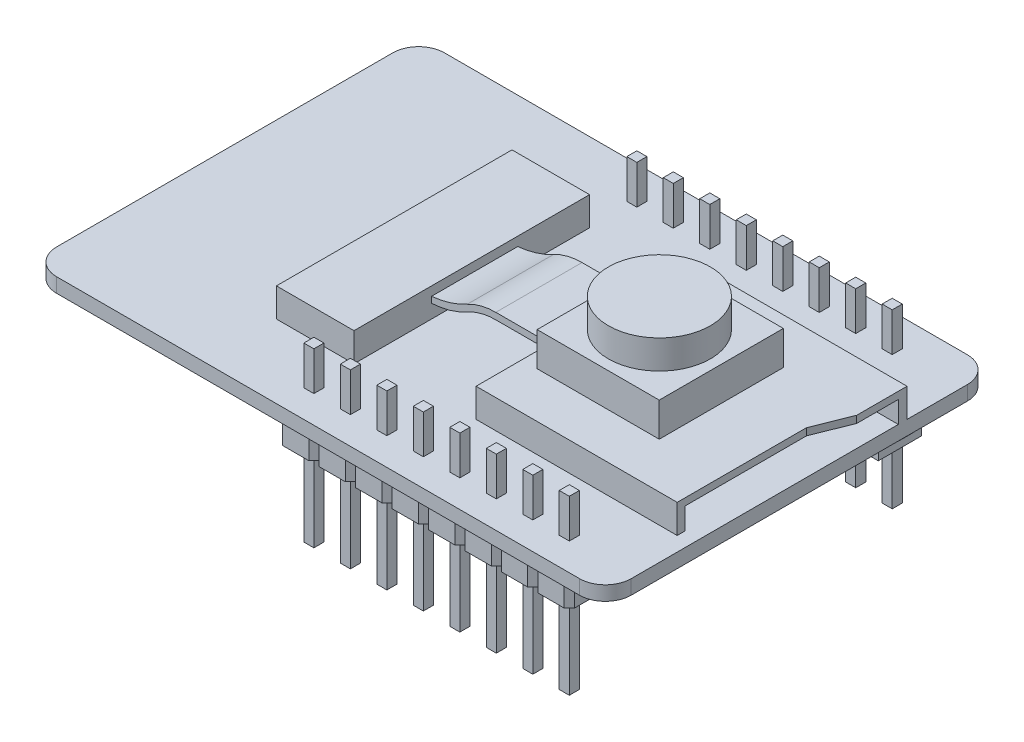
SolidWorks part; units mm, degrees
ref_plane "前视基准面" through (0, 0, 0) normal (0, 0, 1) x (1, 0, 0)
ref_plane "上视基准面" through (0, 0, 0) normal (0, 1, 0) x (1, 0, 0)
ref_plane "右视基准面" through (0, 0, 0) normal (1, 0, 0) x (0, 0, -1)
sketch "草图1" plane through (0, 0, 0) normal (0, 1, 0) x (1, 0, 0)
  line L0 (-20, 13.5) -> (20, 13.5)
  line L1 (-20, 13.5) -> (-20, -13.5)
  line L2 (20, 13.5) -> (20, -13.5)
  line L3 (-20, -13.5) -> (20, -13.5)
  line L4 (-20, 13.5) -> (20, -13.5) construction
  line L5 (20, 13.5) -> (-20, -13.5) construction
  point P1 (0, 0)
extrude "凸台-拉伸1" add sketch "草图1" along normal blind 1
fillet "圆角1" radius 1.8 4 edges at (-20, 0.5, 13.5) (-20, 0.5, -13.5) (20, 0.5, -13.5) (20, 0.5, 13.5)
sketch "草图4" plane through (0, 0, 0) normal (0, -1, 0) x (1, 0, 0)
  line L0 (-20, -11.7) -> (-20, 11.7) construction
  line L1 (-20, 9) -> (5.5, 9)
  line L2 (-20, 9) -> (-20, -9)
  line L3 (-20, -9) -> (5.5, -9)
  line L4 (5.5, 9) -> (5.5, -9)
  line L5 (-24.7231, 0) -> (25.6877, 0) construction
  dimension "D1" = 18
  dimension "D2" = 25.5
extrude "esp32底板" add sketch "草图4" along normal blind 1
sketch "草图5" plane through (0, -1, 0) normal (0, -1, 0) x (1, 0, 0)
  line L0 (-27.2904, 0) -> (11.6436, 0) construction
  line L1 (-12.65, 2.15) -> (-9.41, 2.15)
  line L2 (-12.65, 2.15) -> (-12.65, -7.85)
  line L3 (-12.65, -7.85) -> (-9.0798, -7.85)
  line L5 (-9.41, 7.85) -> (4.35, 7.85)
  line L6 (-9.41, 7.85) -> (-9.41, 2.15)
  line L7 (-9.0798, -7.85) -> (4.35, -7.85)
  line L8 (4.35, 7.85) -> (4.35, -7.85)
  line L9 (5.5, -9) -> (5.5, 9) construction
  dimension "D1" = 10
  dimension "D2" = 15.7
  dimension "D3" = 3.24
  dimension "D4" = 5.7
  dimension "D5" = 17
  dimension "D6" = 1.15
extrude "esp32外壳" add sketch "草图5" along normal blind 2.4
sketch "草图6" plane through (0, -1, 0) normal (0, -1, 0) x (1, 0, 0)
  line L0 (-20, 9) -> (-20, -9) construction
  line L1 (-14, 8) -> (-11.2, 8)
  line L2 (-14, 8) -> (-14, 5.6)
  line L3 (-14, 5.6) -> (-11.2, 5.6)
  line L4 (-11.2, 8) -> (-11.2, 5.6)
  line L5 (5.5, 9) -> (-20, 9) construction
  dimension "D1" = 6
  dimension "D2" = 1
  dimension "D3" = 2.4
  dimension "D4" = 2.8
extrude "天线座子地" add sketch "草图6" along normal blind 0.5
sketch "草图7" plane through (0, -1.5, 0) normal (0, -1, 0) x (1, 0, 0)
  circle A0 centre (-12.6345, 6.845) radius 0.101
extrude "天线座子针" add sketch "草图7" along normal blind 0.5
sketch "草图8" plane through (0, -1.5, 0) normal (0, -1, 0) x (1, 0, 0)
  circle A0 centre (-12.6345, 6.845) radius 1
  circle A1 centre (-12.6345, 6.845) radius 0.7746
  dimension "D1" = 2
extrude "天线座子" add sketch "草图8" along normal blind 0.5
sketch "草图9" plane through (0, -1, 0) normal (0, -1, 0) x (1, 0, 0)
  line L0 (-15.5448, -7.9938) -> (-18.5448, -7.9938)
  line L1 (-18.5448, -7.9938) -> (-18.5448, -4.9938)
  line L2 (-18.5448, -4.9938) -> (-15.5448, -4.9938)
  line L3 (-15.5448, -4.9938) -> (-15.5448, -1.9938)
  line L4 (-15.5448, -1.9938) -> (-18.5448, -1.9938)
  line L5 (-18.5448, -1.9938) -> (-18.5448, 1.0062)
  line L6 (-18.5448, 1.0062) -> (-15.5448, 1.0062)
  line L7 (-15.5448, 1.0062) -> (-15.5448, 4.0062)
  line L8 (-15.5448, 4.0062) -> (-18.5448, 4.0062)
  line L9 (-18.5448, 4.0062) -> (-18.5448, 7.0062)
  line L10 (-18.5448, 7.0062) -> (-15.5448, 7.0062)
  line L11 (-15.5448, 7.0062) -> (-15.5448, 8.3405)
  line L12 (-15.5448, 8.3405) -> (-19.2709, 8.3405)
  line L13 (-19.2709, 8.3405) -> (-19.2709, 3.4012)
  line L14 (-19.2709, 3.4012) -> (-16.0214, 3.4012)
  line L15 (-16.0214, 3.4012) -> (-16.0214, 1.5814)
  line L16 (-16.0214, 1.5814) -> (-19.2709, 1.5814)
  line L17 (-19.2709, 1.5814) -> (-19.2709, -2.7513)
  line L18 (-19.2709, -2.7513) -> (-16.0214, -2.7513)
  line L19 (-16.0214, -2.7513) -> (-16.0214, -4.3977)
  line L20 (-16.0214, -4.3977) -> (-19.2709, -4.3977)
  line L21 (-19.2709, -4.3977) -> (-19.2709, -8.6004)
  line L22 (-19.2709, -8.6004) -> (-13.8983, -8.6004)
  line L23 (-13.8983, -8.6004) -> (-13.8983, -7.9938)
  line L24 (-13.8983, -7.9938) -> (-15.5448, -7.9938)
extrude "天线" add sketch "草图9" along normal blind 0.1
sketch "草图10" plane through (0, 0, 0) normal (0, -1, 0) x (1, 0, 0)
  line L0 (20, 11.7) -> (20, -11.7) construction
  line L1 (12.5, 9.4) -> (16.5, 9.4)
  line L2 (12.5, 9.4) -> (12.5, 4.4)
  line L3 (12.5, 4.4) -> (16.5, 4.4)
  line L4 (16.5, 9.4) -> (16.5, 4.4)
  line L5 (-18.2, 13.5) -> (18.2, 13.5) construction
  dimension "D1" = 4
  dimension "D2" = 5
  dimension "D3" = 3.5
  dimension "D4" = 4.1
extrude "FLASH" add sketch "草图10" along normal blind 1.5
sketch "草图2" plane through (0, 0, 0) normal (0, -1, 0) x (1, 0, 0)
  line L0 (16.5, 19.3459) -> (16.5, -19.7584) construction
  line L5 (20, 11.7) -> (20, -11.7) construction
  line L6 (-3.8208, 12.1566) -> (-3.8208, 10.3237)
  line L7 (-3.8208, 10.3237) -> (-3.4672, 9.9701)
  line L8 (-3.4672, 9.9701) -> (-1.6343, 9.9701)
  line L9 (-1.6343, 9.9701) -> (-1.2808, 10.3237)
  line L11 (-1.2808, 12.1566) -> (-1.6343, 12.5101)
  line L20 (-1.6343, 12.5101) -> (-3.4672, 12.5101)
  line L21 (-3.4672, 12.5101) -> (-3.8208, 12.1566)
  line L24 (0.9057, 12.5101) -> (-0.9272, 12.5101)
  line L25 (1.2592, 12.1566) -> (0.9057, 12.5101)
  line L27 (0.9057, 9.9701) -> (1.2592, 10.3237)
  line L28 (-0.9272, 9.9701) -> (0.9057, 9.9701)
  line L29 (-1.2808, 10.3237) -> (-0.9272, 9.9701)
  line L31 (-0.9272, 12.5101) -> (-1.2808, 12.1566)
  line L32 (3.4457, 12.5101) -> (1.6128, 12.5101)
  line L33 (3.7992, 12.1566) -> (3.4457, 12.5101)
  line L35 (3.4457, 9.9701) -> (3.7992, 10.3237)
  line L36 (1.6128, 9.9701) -> (3.4457, 9.9701)
  line L37 (1.2592, 10.3237) -> (1.6128, 9.9701)
  line L39 (1.6128, 12.5101) -> (1.2592, 12.1566)
  line L40 (5.9857, 12.5101) -> (4.1528, 12.5101)
  line L41 (6.3392, 12.1566) -> (5.9857, 12.5101)
  line L43 (5.9857, 9.9701) -> (6.3392, 10.3237)
  line L44 (4.1528, 9.9701) -> (5.9857, 9.9701)
  line L45 (3.7992, 10.3237) -> (4.1528, 9.9701)
  line L47 (4.1528, 12.5101) -> (3.7992, 12.1566)
  line L48 (8.5257, 12.5101) -> (6.6928, 12.5101)
  line L49 (8.8792, 12.1566) -> (8.5257, 12.5101)
  line L51 (8.5257, 9.9701) -> (8.8792, 10.3237)
  line L52 (6.6928, 9.9701) -> (8.5257, 9.9701)
  line L53 (6.3392, 10.3237) -> (6.6928, 9.9701)
  line L55 (6.6928, 12.5101) -> (6.3392, 12.1566)
  line L56 (11.0657, 12.5101) -> (9.2328, 12.5101)
  line L57 (11.4192, 12.1566) -> (11.0657, 12.5101)
  line L59 (11.0657, 9.9701) -> (11.4192, 10.3237)
  line L60 (9.2328, 9.9701) -> (11.0657, 9.9701)
  line L61 (8.8792, 10.3237) -> (9.2328, 9.9701)
  line L63 (9.2328, 12.5101) -> (8.8792, 12.1566)
  line L64 (13.6057, 12.5101) -> (11.7728, 12.5101)
  line L65 (13.9592, 12.1566) -> (13.6057, 12.5101)
  line L67 (13.6057, 9.9701) -> (13.9592, 10.3237)
  line L68 (11.7728, 9.9701) -> (13.6057, 9.9701)
  line L69 (11.4192, 10.3237) -> (11.7728, 9.9701)
  line L71 (11.7728, 12.5101) -> (11.4192, 12.1566)
  line L72 (16.1457, 12.5101) -> (14.3128, 12.5101)
  line L73 (16.4992, 12.1566) -> (16.1457, 12.5101)
  line L74 (16.4992, 10.3237) -> (16.4992, 12.1566)
  line L75 (16.1457, 9.9701) -> (16.4992, 10.3237)
  line L76 (14.3128, 9.9701) -> (16.1457, 9.9701)
  line L77 (13.9592, 10.3237) -> (14.3128, 9.9701)
  line L79 (14.3128, 12.5101) -> (13.9592, 12.1566)
  line L80 (-30.9826, 0) -> (35.1621, 0) construction
  line L81 (14.3128, -12.5101) -> (13.9592, -12.1566)
  line L83 (13.9592, -10.3237) -> (14.3128, -9.9701)
  line L84 (14.3128, -9.9701) -> (16.1457, -9.9701)
  line L85 (16.1457, -9.9701) -> (16.4992, -10.3237)
  line L86 (16.4992, -10.3237) -> (16.4992, -12.1566)
  line L87 (16.4992, -12.1566) -> (16.1457, -12.5101)
  line L88 (16.1457, -12.5101) -> (14.3128, -12.5101)
  line L89 (11.7728, -12.5101) -> (11.4192, -12.1566)
  line L91 (11.4192, -10.3237) -> (11.7728, -9.9701)
  line L92 (11.7728, -9.9701) -> (13.6057, -9.9701)
  line L93 (13.6057, -9.9701) -> (13.9592, -10.3237)
  line L95 (13.9592, -12.1566) -> (13.6057, -12.5101)
  line L96 (13.6057, -12.5101) -> (11.7728, -12.5101)
  line L97 (9.2328, -12.5101) -> (8.8792, -12.1566)
  line L99 (8.8792, -10.3237) -> (9.2328, -9.9701)
  line L100 (9.2328, -9.9701) -> (11.0657, -9.9701)
  line L101 (11.0657, -9.9701) -> (11.4192, -10.3237)
  line L103 (11.4192, -12.1566) -> (11.0657, -12.5101)
  line L104 (11.0657, -12.5101) -> (9.2328, -12.5101)
  line L105 (6.6928, -12.5101) -> (6.3392, -12.1566)
  line L107 (6.3392, -10.3237) -> (6.6928, -9.9701)
  line L108 (6.6928, -9.9701) -> (8.5257, -9.9701)
  line L109 (8.5257, -9.9701) -> (8.8792, -10.3237)
  line L111 (8.8792, -12.1566) -> (8.5257, -12.5101)
  line L112 (8.5257, -12.5101) -> (6.6928, -12.5101)
  line L113 (4.1528, -12.5101) -> (3.7992, -12.1566)
  line L115 (3.7992, -10.3237) -> (4.1528, -9.9701)
  line L116 (4.1528, -9.9701) -> (5.9857, -9.9701)
  line L117 (5.9857, -9.9701) -> (6.3392, -10.3237)
  line L119 (6.3392, -12.1566) -> (5.9857, -12.5101)
  line L120 (5.9857, -12.5101) -> (4.1528, -12.5101)
  line L121 (1.6128, -12.5101) -> (1.2592, -12.1566)
  line L123 (1.2592, -10.3237) -> (1.6128, -9.9701)
  line L124 (1.6128, -9.9701) -> (3.4457, -9.9701)
  line L125 (3.4457, -9.9701) -> (3.7992, -10.3237)
  line L127 (3.7992, -12.1566) -> (3.4457, -12.5101)
  line L128 (3.4457, -12.5101) -> (1.6128, -12.5101)
  line L129 (-0.9272, -12.5101) -> (-1.2808, -12.1566)
  line L131 (-1.2808, -10.3237) -> (-0.9272, -9.9701)
  line L132 (-0.9272, -9.9701) -> (0.9057, -9.9701)
  line L133 (0.9057, -9.9701) -> (1.2592, -10.3237)
  line L135 (1.2592, -12.1566) -> (0.9057, -12.5101)
  line L136 (0.9057, -12.5101) -> (-0.9272, -12.5101)
  line L137 (-3.4672, -12.5101) -> (-3.8208, -12.1566)
  line L138 (-1.6343, -12.5101) -> (-3.4672, -12.5101)
  line L139 (-1.2808, -12.1566) -> (-1.6343, -12.5101)
  line L141 (-1.6343, -9.9701) -> (-1.2808, -10.3237)
  line L142 (-3.4672, -9.9701) -> (-1.6343, -9.9701)
  line L143 (-3.8208, -10.3237) -> (-3.4672, -9.9701)
  line L144 (-3.8208, -12.1566) -> (-3.8208, -10.3237)
  line L145 (-1.2808, 12.1566) -> (-1.2808, 10.3237) [skipped]
  line L146 (1.2592, 12.1566) -> (1.2592, 10.3237) [skipped]
  line L147 (3.7992, 12.1566) -> (3.7992, 10.3237) [skipped]
  line L148 (6.3392, 12.1566) -> (6.3392, 10.3237) [skipped]
  line L149 (8.8792, 12.1566) -> (8.8792, 10.3237) [skipped]
  line L150 (11.4192, 12.1566) -> (11.4192, 10.3237) [skipped]
  line L151 (13.9592, 12.1566) -> (13.9592, 10.3237) [skipped]
  point P10 (16.6244, -19.7584)
  dimension "D2" = 3.5
  dimension "D10" = 8
extrude "排针座" add sketch "草图2" along normal blind 2.3
sketch "草图3" plane through (0, -2.3, 0) normal (0, -1, 0) x (1, 0, 0)
  line L0 (-2.5508, 14.1529) -> (-2.5508, 9.1716) construction
  line L1 (-2.9008, 11.5901) -> (-2.2008, 11.5901)
  line L2 (-2.9008, 11.5901) -> (-2.9008, 10.8901)
  line L3 (-2.9008, 10.8901) -> (-2.2008, 10.8901)
  line L4 (-2.2008, 11.5901) -> (-2.2008, 10.8901)
  line L5 (-17.9073, 11.2401) -> (-15.9733, 11.2401) construction
  line L6 (-0.3608, 11.5901) -> (-0.3608, 10.8901)
  line L7 (-0.3608, 11.5901) -> (0.3392, 11.5901)
  line L8 (0.3392, 11.5901) -> (0.3392, 10.8901)
  line L9 (-0.3608, 10.8901) -> (0.3392, 10.8901)
  line L10 (2.1792, 11.5901) -> (2.1792, 10.8901)
  line L11 (2.1792, 11.5901) -> (2.8792, 11.5901)
  line L12 (2.8792, 11.5901) -> (2.8792, 10.8901)
  line L13 (2.1792, 10.8901) -> (2.8792, 10.8901)
  line L14 (4.7192, 11.5901) -> (4.7192, 10.8901)
  line L15 (4.7192, 11.5901) -> (5.4192, 11.5901)
  line L16 (5.4192, 11.5901) -> (5.4192, 10.8901)
  line L17 (4.7192, 10.8901) -> (5.4192, 10.8901)
  line L18 (7.2592, 11.5901) -> (7.2592, 10.8901)
  line L19 (7.2592, 11.5901) -> (7.9592, 11.5901)
  line L20 (7.9592, 11.5901) -> (7.9592, 10.8901)
  line L21 (7.2592, 10.8901) -> (7.9592, 10.8901)
  line L22 (9.7992, 11.5901) -> (9.7992, 10.8901)
  line L23 (9.7992, 11.5901) -> (10.4992, 11.5901)
  line L24 (10.4992, 11.5901) -> (10.4992, 10.8901)
  line L25 (9.7992, 10.8901) -> (10.4992, 10.8901)
  line L26 (12.3392, 11.5901) -> (12.3392, 10.8901)
  line L27 (12.3392, 11.5901) -> (13.0392, 11.5901)
  line L28 (13.0392, 11.5901) -> (13.0392, 10.8901)
  line L29 (12.3392, 10.8901) -> (13.0392, 10.8901)
  line L30 (14.8792, 11.5901) -> (14.8792, 10.8901)
  line L31 (14.8792, 11.5901) -> (15.5792, 11.5901)
  line L32 (15.5792, 11.5901) -> (15.5792, 10.8901)
  line L33 (14.8792, 10.8901) -> (15.5792, 10.8901)
  line L34 (-25.7488, 0) -> (27.3099, 0) construction
  line L35 (-2.9008, -10.8901) -> (-2.2008, -10.8901)
  line L36 (-2.9008, -11.5901) -> (-2.9008, -10.8901)
  line L37 (-2.9008, -11.5901) -> (-2.2008, -11.5901)
  line L38 (-2.2008, -11.5901) -> (-2.2008, -10.8901)
  line L39 (14.8792, -10.8901) -> (15.5792, -10.8901)
  line L40 (15.5792, -11.5901) -> (15.5792, -10.8901)
  line L41 (14.8792, -11.5901) -> (15.5792, -11.5901)
  line L42 (14.8792, -11.5901) -> (14.8792, -10.8901)
  line L43 (12.3392, -10.8901) -> (13.0392, -10.8901)
  line L44 (13.0392, -11.5901) -> (13.0392, -10.8901)
  line L45 (12.3392, -11.5901) -> (13.0392, -11.5901)
  line L46 (12.3392, -11.5901) -> (12.3392, -10.8901)
  line L47 (9.7992, -10.8901) -> (10.4992, -10.8901)
  line L48 (10.4992, -11.5901) -> (10.4992, -10.8901)
  line L49 (9.7992, -11.5901) -> (10.4992, -11.5901)
  line L50 (9.7992, -11.5901) -> (9.7992, -10.8901)
  line L51 (7.2592, -10.8901) -> (7.9592, -10.8901)
  line L52 (7.9592, -11.5901) -> (7.9592, -10.8901)
  line L53 (7.2592, -11.5901) -> (7.9592, -11.5901)
  line L54 (7.2592, -11.5901) -> (7.2592, -10.8901)
  line L55 (4.7192, -10.8901) -> (5.4192, -10.8901)
  line L56 (5.4192, -11.5901) -> (5.4192, -10.8901)
  line L57 (4.7192, -11.5901) -> (5.4192, -11.5901)
  line L58 (4.7192, -11.5901) -> (4.7192, -10.8901)
  line L59 (2.1792, -10.8901) -> (2.8792, -10.8901)
  line L60 (2.8792, -11.5901) -> (2.8792, -10.8901)
  line L61 (2.1792, -11.5901) -> (2.8792, -11.5901)
  line L62 (2.1792, -11.5901) -> (2.1792, -10.8901)
  line L63 (-0.3608, -10.8901) -> (0.3392, -10.8901)
  line L64 (0.3392, -11.5901) -> (0.3392, -10.8901)
  line L65 (-0.3608, -11.5901) -> (0.3392, -11.5901)
  line L66 (-0.3608, -11.5901) -> (-0.3608, -10.8901)
  dimension "D1" = 0.7
  dimension "D2" = 8
extrude "排针" add sketch "草图3" along normal mid plane 12
sketch "草图11" plane through (0, 0, 0) normal (0, -1, 0) x (1, 0, 0)
  line L0 (20, 11.7) -> (20, -11.7) construction
  line L1 (13.5, 2) -> (17, 2)
  line L2 (13.5, 2) -> (13.5, -4.5)
  line L3 (13.5, -4.5) -> (17, -4.5)
  line L4 (17, 2) -> (17, -4.5)
  line L6 (12.5, 4.4) -> (16.5, 4.4) construction
  dimension "D1" = 3.5
  dimension "D2" = 6.5
  dimension "D3" = 3
  dimension "D4" = 2.4
extrude "AMS1117" add sketch "草图11" along normal blind 1.5
sketch "草图12" plane through (0, 0, 0) normal (0, -1, 0) x (1, 0, 0)
  line L0 (20, 11.7) -> (20, -11.7) construction
  line L1 (15, -6.5) -> (19, -6.5)
  line L2 (15, -6.5) -> (15, -9.5)
  line L3 (15, -9.5) -> (19, -9.5)
  line L4 (19, -6.5) -> (19, -9.5)
  line L5 (18.2, -13.5) -> (-18.2, -13.5) construction
  dimension "D1" = 4
  dimension "D2" = 3
  dimension "D3" = 1
  dimension "D4" = 4
extrude "按键" add sketch "草图12" along normal blind 1.5
sketch "草图13" plane through (0, -1.5, 0) normal (0, -1, 0) x (1, 0, 0)
  line L0 (19, -9.5) -> (19, -6.5) construction
  line L1 (15, -9.5) -> (19, -9.5) construction
  circle A0 centre (17, -8) radius 0.8706
  point P2 (16.9883, -8.0347)
  dimension "D1" = 2
  dimension "D2" = 1.5
extrude "按键按键" add sketch "草图13" along normal blind 0.5
sketch "草图14" plane through (0, 0, 0) normal (0, -1, 0) x (1, 0, 0)
  line L0 (17, -4.5) -> (17, 2) construction
  line L1 (17, 0.5049) -> (18.7364, 0.5049)
  line L2 (17, 0.5049) -> (17, -2.8731)
  line L3 (17, -2.8731) -> (18.7364, -2.8731)
  line L4 (18.7364, 0.5049) -> (18.7364, -2.8731)
  line L5 (13.5, 2) -> (13.5, -4.5) construction
  line L6 (13.5, 1.4088) -> (11.4048, 1.4088)
  line L7 (13.5, 1.4088) -> (13.5, 0.4088)
  line L8 (13.5, 0.4088) -> (11.4048, 0.4088)
  line L9 (11.4048, 1.4088) -> (11.4048, 0.4088)
  line L10 (11.4048, 3.1692) -> (11.4048, -4.8238) construction
  line L11 (13.5038, -0.6603) -> (11.4086, -0.6603)
  line L12 (13.5038, -0.6603) -> (13.5038, -1.6603)
  line L13 (13.5038, -1.6603) -> (11.4086, -1.6603)
  line L14 (11.4086, -0.6603) -> (11.4086, -1.6603)
  line L15 (13.5038, -2.7538) -> (11.4086, -2.7538)
  line L16 (13.5038, -2.7538) -> (13.5038, -3.7538)
  line L17 (13.5038, -3.7538) -> (11.4086, -3.7538)
  line L18 (11.4086, -2.7538) -> (11.4086, -3.7538)
  line L19 (14.5, 8.9826) -> (14.5, 5.1892) construction
  line L20 (18.2667, 9.8153) -> (18.2667, 3.385) construction
  line L21 (16.5, 4.4) -> (16.5, 9.4) construction
  line L22 (16.5, 9.0521) -> (18.2667, 9.0521)
  line L23 (16.5, 9.0521) -> (16.5, 8.4738)
  line L24 (16.5, 8.4738) -> (18.2667, 8.4738)
  line L25 (18.2667, 9.0521) -> (18.2667, 8.4738)
  line L26 (16.5, 4.4) -> (16.5, 9.4) construction
  line L27 (16.5, 7.922) -> (18.2667, 7.922)
  line L28 (16.5, 7.922) -> (16.5, 7.3437)
  line L29 (16.5, 7.3437) -> (18.2667, 7.3437)
  line L30 (18.2667, 7.922) -> (18.2667, 7.3437)
  line L31 (16.5, 6.6234) -> (18.2667, 6.6234)
  line L32 (16.5, 6.6234) -> (16.5, 6.0451)
  line L33 (16.5, 6.0451) -> (18.2667, 6.0451)
  line L34 (18.2667, 6.6234) -> (18.2667, 6.0451)
  line L35 (16.5, 5.3875) -> (18.2667, 5.3875)
  line L36 (16.5, 5.3875) -> (16.5, 4.8093)
  line L37 (16.5, 4.8093) -> (18.2667, 4.8093)
  line L38 (18.2667, 5.3875) -> (18.2667, 4.8093)
  line L39 (12.5, 9.4) -> (12.5, 4.4) construction
  line L40 (12.5, 4.8093) -> (10.7333, 4.8093)
  line L41 (10.7333, 5.3875) -> (10.7333, 4.8093)
  line L42 (12.5, 5.3875) -> (10.7333, 5.3875)
  line L43 (12.5, 5.3875) -> (12.5, 4.8093)
  line L44 (12.5, 6.0451) -> (10.7333, 6.0451)
  line L45 (10.7333, 6.6234) -> (10.7333, 6.0451)
  line L46 (12.5, 6.6234) -> (10.7333, 6.6234)
  line L47 (12.5, 6.6234) -> (12.5, 6.0451)
  line L48 (12.5, 7.3437) -> (10.7333, 7.3437)
  line L49 (10.7333, 7.922) -> (10.7333, 7.3437)
  line L50 (12.5, 7.922) -> (10.7333, 7.922)
  line L51 (12.5, 7.922) -> (12.5, 7.3437)
  line L52 (12.5, 8.4738) -> (10.7333, 8.4738)
  line L53 (10.7333, 9.0521) -> (10.7333, 8.4738)
  line L54 (12.5, 9.0521) -> (10.7333, 9.0521)
  line L55 (12.5, 9.0521) -> (12.5, 8.4738)
  line L56 (15, -6.5) -> (15, -9.5) construction
  line L57 (15, -7.4368) -> (14.5, -7.4368)
  line L58 (15, -7.4368) -> (15, -8.4368)
  line L59 (15, -8.4368) -> (14.5, -8.4368)
  line L60 (14.5, -7.4368) -> (14.5, -8.4368)
  line L61 (19, -9.5) -> (19, -6.5) construction
  line L62 (19, -7.4368) -> (19.5118, -7.4368)
  line L63 (19, -7.4368) -> (19, -8.4368)
  line L64 (19, -8.4368) -> (19.5118, -8.4368)
  line L65 (19.5118, -7.4368) -> (19.5118, -8.4368)
extrude "引脚" add sketch "草图14" along normal blind 0.5
sketch "草图15" plane through (0, 1, 0) normal (0, 1, 0) x (1, 0, 0)
  line L1 (5, 7.5) -> (5, -7.5)
  line L2 (5, -7.5) -> (19, -7.5)
  line L3 (19, -7.5) -> (19, 1.5)
  line L4 (19, 1.5) -> (20, 4)
  line L5 (20, 4) -> (20, 7.5)
  line L6 (20, 7.5) -> (5, 7.5)
  line L7 (20, -11.7) -> (20, 11.7) construction
  line L8 (18.2, 13.5) -> (-18.2, 13.5) construction
  dimension "D1" = 15
  dimension "D2" = 15
  dimension "D3" = 14
  dimension "D4" = 9
  dimension "D5" = 3.5
  dimension "D6" = 6
extrude "SD卡" add sketch "草图15" along normal blind 2
sketch "草图16" plane through (20, 0, 0) normal (1, 0, 0) x (0, 0, -1)
  line L0 (-7.5, 1) -> (1.5, 1) construction
  line L1 (6.8932, 2.5068) -> (-6.9498, 2.5068)
  line L2 (6.8932, 2.5068) -> (6.8932, 1)
  line L3 (6.8932, 1) -> (-6.9498, 1)
  line L4 (-6.9498, 2.5068) -> (-6.9498, 1)
extrude "SD卡掏空" cut sketch "草图16" against normal blind 14
sketch "草图17" plane through (0, 3, 0) normal (0, 1, 0) x (1, 0, 0)
  line L0 (-10.8413, 0) -> (2.6212, 0) construction
  line L1 (6.0703, 4.32) -> (14.5703, 4.32)
  line L2 (6.0703, 4.32) -> (6.0703, -4.32)
  line L3 (6.0703, -4.32) -> (14.5703, -4.32)
  line L4 (14.5703, 4.32) -> (14.5703, -4.32)
  dimension "D1" = 8.5
  dimension "D2" = 8.64
extrude "OV2640" add sketch "草图17" along normal blind 2.36
sketch "草图18" plane through (0, 5.36, 0) normal (0, 1, 0) x (1, 0, 0)
  line L2 (14.5703, -4.32) -> (14.5703, 4.32) construction
  circle A0 centre (10.3203, -0.0597) radius 3.55
  point P2 (0, 0)
  dimension "D1" = 7.1
  dimension "D2" = 4.25
extrude "OV2640镜头" add sketch "草图18" along normal blind 2
sketch "草图19" plane through (0, 1, 0) normal (0, 1, 0) x (1, 0, 0)
  line L0 (18.2, 13.5) -> (-18.2, 13.5) construction
  line L1 (-8, 8) -> (-2.6, 8)
  line L2 (-8, 8) -> (-8, -8.4)
  line L3 (-8, -8.4) -> (-2.6, -8.4)
  line L4 (-2.6, 8) -> (-2.6, -8.4)
  line L5 (-20, 11.7) -> (-20, -11.7) construction
  dimension "D1" = 16.4
  dimension "D2" = 5.4
  dimension "D3" = 5.5
  dimension "D4" = 12
extrude "凸台-拉伸18" add sketch "草图19" along normal blind 2
sketch "草图20" plane through (0, 0, 0) normal (0, 0, 1) x (1, 0, 0)
  line L0 (6.0703, 3.6432) -> (1.8743, 3.6432)
  line L1 (6.0703, 5.36) -> (6.0703, 3) construction
  line L2 (-2.9008, 1) -> (-2.9008, 3.7) construction
  line L3 (-2.9008, 2.35) -> (-2.9008, 1.9429)
  line L4 (1.8743, 3.1881) -> (6.0703, 3.1881)
  line L5 (6.0703, 3.1881) -> (6.0703, 3.6432)
  arc A0 (1.8743, 3.6432) -> (-0.1139, 3.1359) centre (1.8743, -0.5062) ccw
  arc A1 (-0.1139, 3.1359) -> (-2.9008, 2.35) centre (-3.2254, 8.8358) cw
  arc A2 (-2.9008, 1.9429) -> (-0.1139, 2.6697) centre (-2.9008, 7.65) ccw
  arc A3 (-0.1139, 2.6697) -> (1.8743, 3.1881) centre (1.8743, -0.8834) cw
extrude "凸台-拉伸19" add sketch "草图20" along normal mid plane 6
